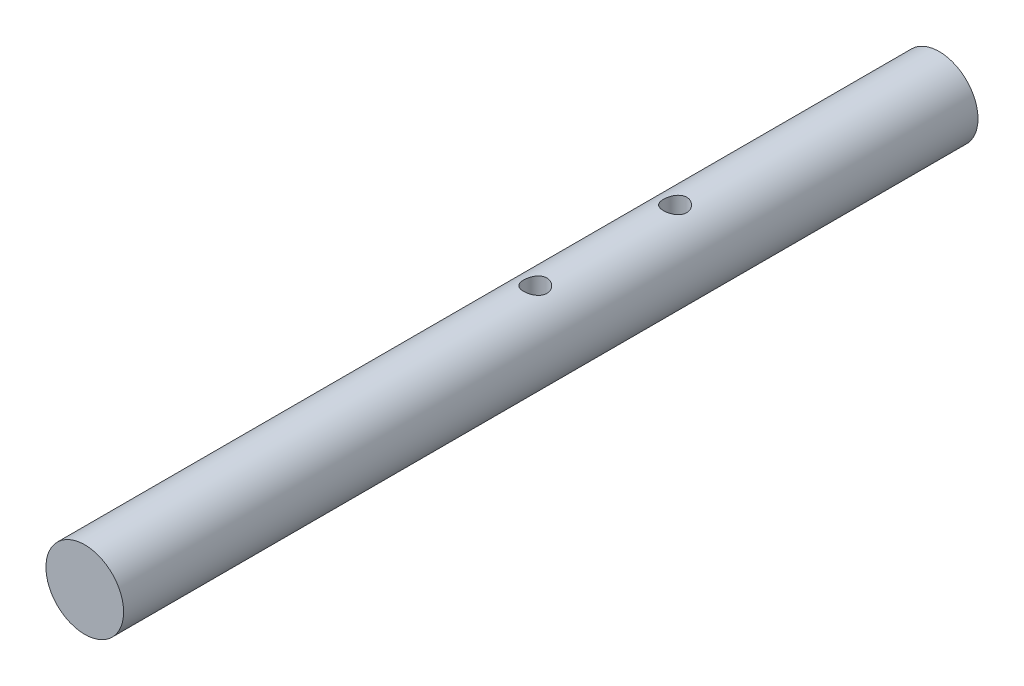
SolidWorks part; units mm, degrees
ref_plane "Front Plane" through (0, 0, 0) normal (0, 0, 1) x (1, 0, 0)
ref_plane "Top Plane" through (0, 0, 0) normal (0, 1, 0) x (1, 0, 0)
ref_plane "Right Plane" through (0, 0, 0) normal (1, 0, 0) x (0, 0, -1)
sketch "Sketch1" plane through (0, 0, 0) normal (0, 0, 1) x (1, 0, 0)
  circle A0 centre (0, 0) radius 5
  dimension "D1" = 10
extrude "Boss-Extrude1" add sketch "Sketch1" along normal mid plane 110
sketch "Sketch2" plane through (0, 0, 0) normal (0, 1, 0) x (1, 0, 0)
  line L0 (5, 55) -> (-5, 55) construction
  circle A0 centre (0, 21) radius 1.5
  circle A1 centre (0, 3) radius 1.5
  point P6 (0, 0)
  dimension "D1" = 3
  dimension "D2" = 3
  dimension "D3" = 18
  dimension "D4" = 34
extrude "Cut-Extrude1" cut sketch "Sketch2" against normal through all both and the other way through all
